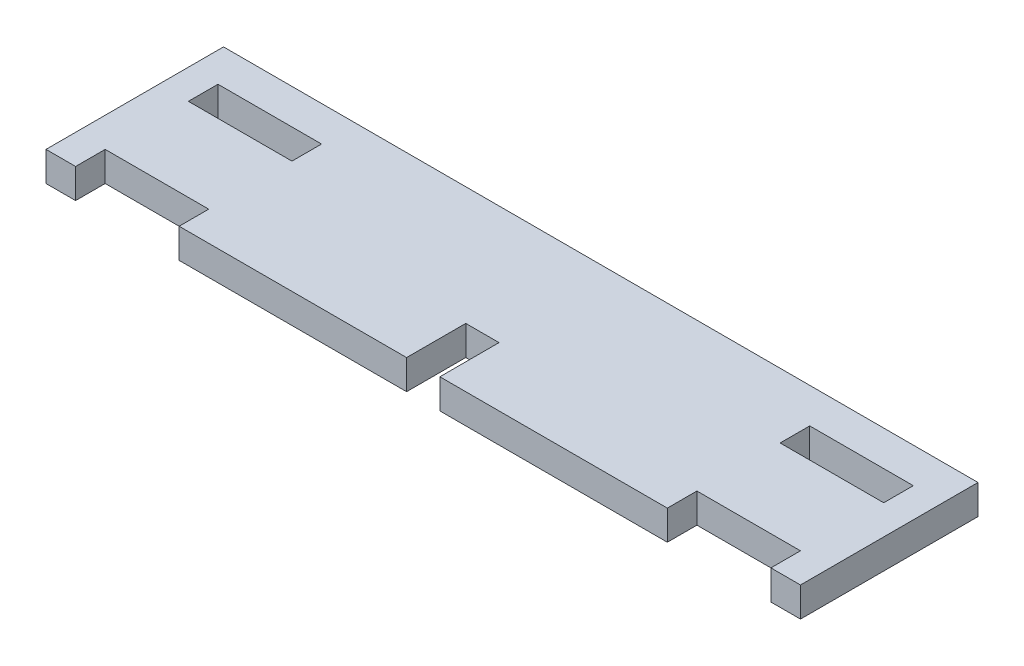
SolidWorks part; units mm, degrees
ref_plane "Front Plane" through (0, 0, 0) normal (0, 0, 1) x (1, 0, 0)
ref_plane "Top Plane" through (0, 0, 0) normal (0, 1, 0) x (1, 0, 0)
ref_plane "Right Plane" through (0, 0, 0) normal (1, 0, 0) x (0, 0, -1)
sketch "Sketch1" plane through (0, 0, 0) normal (0, 1, 0) x (1, 0, 0)
  line L0 (0, 13.9687) -> (0, -15.1029) construction
  line L1 (-51, 12) -> (51, 12)
  line L2 (-51, 12) -> (-51, -12)
  line L3 (-51, -12) -> (51, -12)
  line L4 (51, 12) -> (51, -12)
  line L5 (-51, 12) -> (51, -12) construction
  line L6 (-51, -12) -> (51, 12) construction
  line L7 (33, 7.25) -> (47, 7.25)
  line L8 (33, 7.25) -> (33, 3.25)
  line L9 (33, 3.25) -> (47, 3.25)
  line L10 (47, 7.25) -> (47, 3.25)
  line L11 (33, 7.25) -> (47, 3.25) construction
  line L12 (33, 3.25) -> (47, 7.25) construction
  line L13 (33, -8) -> (47, -8)
  line L14 (33, -8) -> (33, -12)
  line L15 (33, -12) -> (47, -12)
  line L16 (47, -8) -> (47, -12)
  line L17 (-33, 3.25) -> (-47, 7.25) construction
  line L18 (-33, 7.25) -> (-47, 3.25) construction
  line L19 (-47, -8) -> (-47, -12)
  line L20 (-33, -12) -> (-47, -12)
  line L21 (-33, -8) -> (-33, -12)
  line L22 (-33, -8) -> (-47, -8)
  line L23 (-47, 7.25) -> (-47, 3.25)
  line L24 (-33, 3.25) -> (-47, 3.25)
  line L25 (-33, 7.25) -> (-33, 3.25)
  line L26 (-33, 7.25) -> (-47, 7.25)
  line L28 (-2.25, -4) -> (2.25, -4)
  line L29 (-2.25, -4) -> (-2.25, -12)
  line L30 (-2.25, -12) -> (2.25, -12)
  line L31 (2.25, -4) -> (2.25, -12)
  line L32 (-2.25, -4) -> (2.25, -12) construction
  line L33 (-2.25, -12) -> (2.25, -4) construction
  point P0 (0, 0)
  point P6 (40, 5.25)
  point P25 (-40, 5.25)
  point P26 (0, -8)
  dimension "D1" = 24
  dimension "D2" = 102
  dimension "D3" = 14
  dimension "D4" = 4
  dimension "D5" = 4
  dimension "D6" = 4.75
  dimension "D7" = 4
  dimension "D8" = 14
  dimension "D9" = 4
  dimension "D10" = 4.5
  dimension "D11" = 8
extrude "Boss-Extrude1" add sketch "Sketch1" along normal blind 4 contours L28 L31 L3 L14 L13 L16 L4 L1 L2 L19 L22 L21 L29 L26 L25 L24 L23 L7 L10 L9 L8
